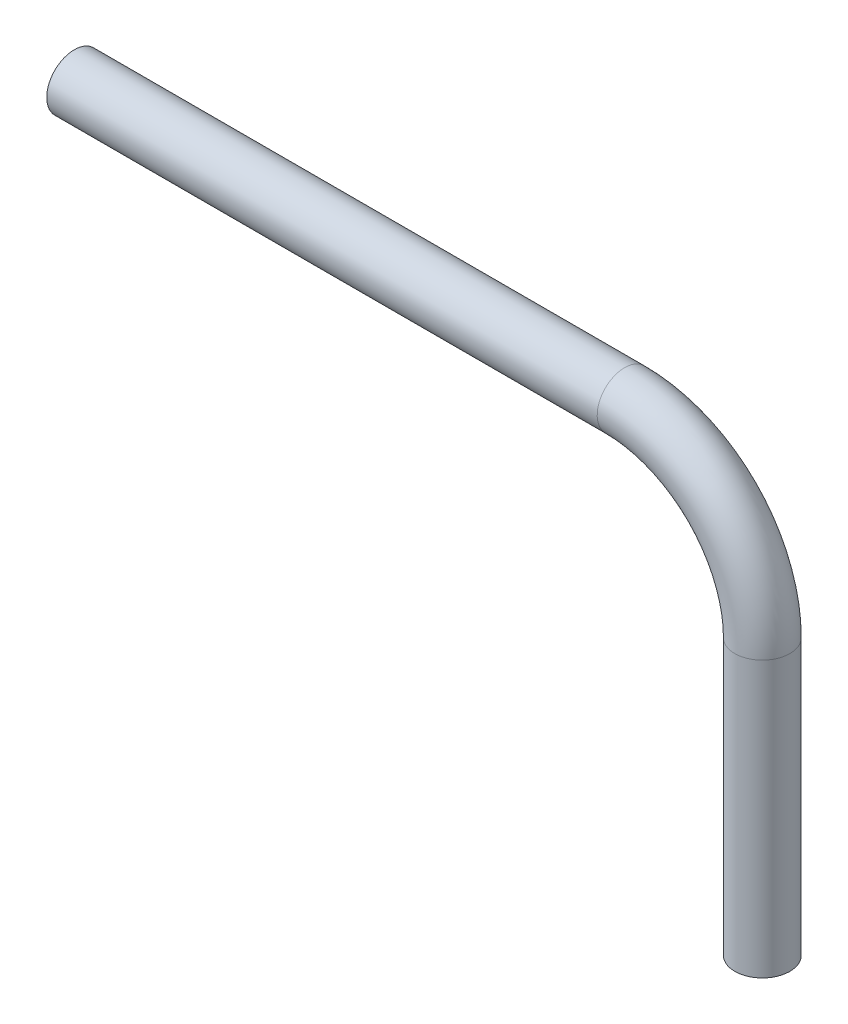
SolidWorks part; units mm, degrees
ref_plane "Front Plane" through (0, 0, 0) normal (0, 0, 1) x (1, 0, 0)
ref_plane "Top Plane" through (0, 0, 0) normal (0, 1, 0) x (1, 0, 0)
ref_plane "Right Plane" through (0, 0, 0) normal (1, 0, 0) x (0, 0, -1)
sketch "Sketch1" plane through (0, 0, 0) normal (0, 0, 1) x (1, 0, 0)
  line L0 (0, 0) -> (100, 0)
  line L3 (125, -25) -> (125, -75)
  line L4 (125, -75) -> (125, -25)
  arc A0 (100, 0) -> (125, -25) centre (100, -25) cw
  point P6 (0, 0)
  dimension "D2" = 125
  dimension "D1" = 25
  dimension "D3" = 75
sketch "Sketch2" plane through (0, 0, 0) normal (1, 0, 0) x (0, 0, -1)
  circle A0 centre (0, 0) radius 5
  point P2 (0, 0)
  point P3 (0, 0)
  point P5 (0, 0)
  dimension "D1" = 10
sweep "Sweep1" add profiles "Sketch2" path "Sketch1"
